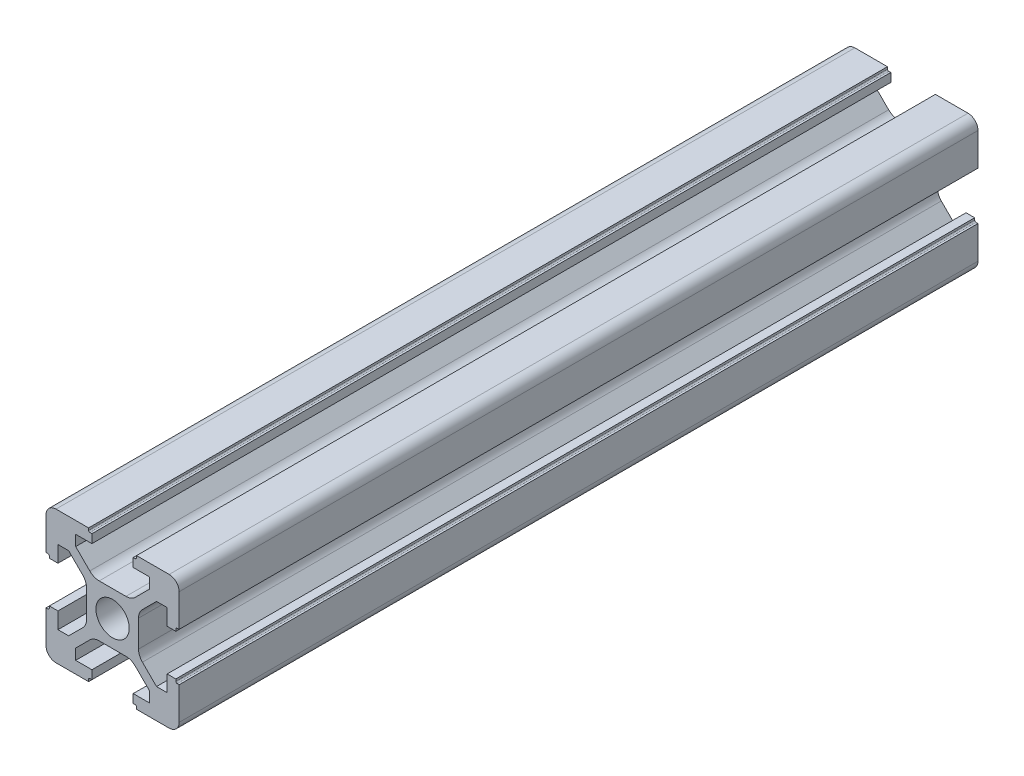
SolidWorks part; units mm, degrees
ref_plane "Спереди" through (0, 0, 0) normal (0, 0, 1) x (1, 0, 0)
ref_plane "Сверху" through (0, 0, 0) normal (0, 1, 0) x (1, 0, 0)
ref_plane "Справа" through (0, 0, 0) normal (1, 0, 0) x (0, 0, -1)
sketch "Sketch1" plane through (0, 0, 0) normal (0, 0, 1) x (1, 0, 0)
  line L0 (0, 10) -> (0, -10) construction
  line L1 (-10, -10) -> (10, -10) construction
  line L2 (-10, -10) -> (-10, 10) construction
  line L3 (-10, 10) -> (10, 10) construction
  line L4 (10, -10) -> (10, 10) construction
  line L5 (-10, -10) -> (10, 10) construction
  line L6 (-10, 10) -> (10, -10) construction
  line L7 (-10, 0) -> (10, 0) construction
  line L8 (0, 3.9) -> (-2.0109, 3.9)
  line L9 (-3.4251, 4.4858) -> (-5.5393, 6.6)
  line L10 (-5.5393, 6.6) -> (-5.5393, 8.2)
  line L11 (-5.5393, 8.2) -> (-3.1, 8.2)
  line L12 (-3.1, 8.2) -> (-3.1, 9.5)
  line L13 (-3.1, 9.5) -> (-3.4, 9.5)
  line L14 (-3.6, 9.7) -> (-3.6, 10)
  line L15 (-3.6, 10) -> (-8.5, 10)
  line L16 (-10, 3.6) -> (-10, 8.5)
  line L17 (-9.7, 3.6) -> (-10, 3.6)
  line L18 (-9.5, 3.1) -> (-9.5, 3.4)
  line L19 (-8.2, 3.1) -> (-9.5, 3.1)
  line L20 (-8.2, 5.5393) -> (-8.2, 3.1)
  line L21 (-6.6, 5.5393) -> (-8.2, 5.5393)
  line L22 (-4.4858, 3.4251) -> (-6.6, 5.5393)
  line L23 (-3.9, 0) -> (-3.9, 2.0109)
  line L24 (3.9, 0) -> (3.9, 2.0109)
  line L25 (4.4858, 3.4251) -> (6.6, 5.5393)
  line L26 (6.6, 5.5393) -> (8.2, 5.5393)
  line L27 (8.2, 5.5393) -> (8.2, 3.1)
  line L28 (8.2, 3.1) -> (9.5, 3.1)
  line L29 (9.5, 3.1) -> (9.5, 3.4)
  line L30 (9.7, 3.6) -> (10, 3.6)
  line L31 (10, 3.6) -> (10, 8.5)
  line L32 (3.6, 10) -> (8.5, 10)
  line L33 (3.6, 9.7) -> (3.6, 10)
  line L34 (3.1, 9.5) -> (3.4, 9.5)
  line L35 (3.1, 8.2) -> (3.1, 9.5)
  line L36 (5.5393, 8.2) -> (3.1, 8.2)
  line L37 (5.5393, 6.6) -> (5.5393, 8.2)
  line L38 (3.4251, 4.4858) -> (5.5393, 6.6)
  line L39 (0, 3.9) -> (2.0109, 3.9)
  line L40 (0, -3.9) -> (2.0109, -3.9)
  line L41 (3.4251, -4.4858) -> (5.5393, -6.6)
  line L42 (5.5393, -6.6) -> (5.5393, -8.2)
  line L43 (5.5393, -8.2) -> (3.1, -8.2)
  line L44 (3.1, -8.2) -> (3.1, -9.5)
  line L45 (3.1, -9.5) -> (3.4, -9.5)
  line L46 (3.6, -9.7) -> (3.6, -10)
  line L47 (3.6, -10) -> (8.5, -10)
  line L48 (10, -3.6) -> (10, -8.5)
  line L49 (9.7, -3.6) -> (10, -3.6)
  line L50 (9.5, -3.1) -> (9.5, -3.4)
  line L51 (8.2, -3.1) -> (9.5, -3.1)
  line L52 (8.2, -5.5393) -> (8.2, -3.1)
  line L53 (6.6, -5.5393) -> (8.2, -5.5393)
  line L54 (4.4858, -3.4251) -> (6.6, -5.5393)
  line L55 (3.9, 0) -> (3.9, -2.0109)
  line L56 (-3.9, 0) -> (-3.9, -2.0109)
  line L57 (-4.4858, -3.4251) -> (-6.6, -5.5393)
  line L58 (-6.6, -5.5393) -> (-8.2, -5.5393)
  line L59 (-8.2, -5.5393) -> (-8.2, -3.1)
  line L60 (-8.2, -3.1) -> (-9.5, -3.1)
  line L61 (-9.5, -3.1) -> (-9.5, -3.4)
  line L62 (-9.7, -3.6) -> (-10, -3.6)
  line L63 (-10, -3.6) -> (-10, -8.5)
  line L64 (-3.6, -10) -> (-8.5, -10)
  line L65 (-3.6, -9.7) -> (-3.6, -10)
  line L66 (-3.1, -9.5) -> (-3.4, -9.5)
  line L67 (-3.1, -8.2) -> (-3.1, -9.5)
  line L68 (-5.5393, -8.2) -> (-3.1, -8.2)
  line L69 (-5.5393, -6.6) -> (-5.5393, -8.2)
  line L70 (-3.4251, -4.4858) -> (-5.5393, -6.6)
  line L71 (0, -3.9) -> (-2.0109, -3.9)
  circle A0 centre (0, 0) radius 2.5
  arc A1 (-8.5, 10) -> (-10, 8.5) centre (-8.5, 8.5) ccw
  arc A2 (-2.0109, 3.9) -> (-3.4251, 4.4858) centre (-2.0109, 5.9) cw
  arc A3 (-3.4, 9.5) -> (-3.6, 9.7) centre (-3.4, 9.7) cw
  arc A4 (-9.5, 3.4) -> (-9.7, 3.6) centre (-9.7, 3.4) ccw
  arc A5 (-3.9, 2.0109) -> (-4.4858, 3.4251) centre (-5.9, 2.0109) ccw
  arc A6 (10, 8.5) -> (8.5, 10) centre (8.5, 8.5) ccw
  arc A7 (3.9, 2.0109) -> (4.4858, 3.4251) centre (5.9, 2.0109) cw
  arc A8 (9.5, 3.4) -> (9.7, 3.6) centre (9.7, 3.4) cw
  arc A9 (3.4, 9.5) -> (3.6, 9.7) centre (3.4, 9.7) ccw
  arc A10 (2.0109, 3.9) -> (3.4251, 4.4858) centre (2.0109, 5.9) ccw
  arc A11 (8.5, -10) -> (10, -8.5) centre (8.5, -8.5) ccw
  arc A12 (2.0109, -3.9) -> (3.4251, -4.4858) centre (2.0109, -5.9) cw
  arc A13 (3.4, -9.5) -> (3.6, -9.7) centre (3.4, -9.7) cw
  arc A14 (9.5, -3.4) -> (9.7, -3.6) centre (9.7, -3.4) ccw
  arc A15 (3.9, -2.0109) -> (4.4858, -3.4251) centre (5.9, -2.0109) ccw
  arc A16 (-10, -8.5) -> (-8.5, -10) centre (-8.5, -8.5) ccw
  arc A17 (-3.9, -2.0109) -> (-4.4858, -3.4251) centre (-5.9, -2.0109) cw
  arc A18 (-9.5, -3.4) -> (-9.7, -3.6) centre (-9.7, -3.4) cw
  arc A19 (-3.4, -9.5) -> (-3.6, -9.7) centre (-3.4, -9.7) ccw
  arc A20 (-2.0109, -3.9) -> (-3.4251, -4.4858) centre (-2.0109, -5.9) ccw
  point P0 (0, 0)
  point P42 (0, 0)
  point P70 (0, 0)
  point P98 (0, 0)
  point P126 (0, 0)
  dimension "D3" = 5
  dimension "D4" = 3
  dimension "D12" = 2
  dimension "D13" = 0.2
  dimension "D1" = 20
  dimension "D2" = 20
  dimension "D5" = 6.2
  dimension "D6" = 7.2
  dimension "D7" = 1.8
  dimension "D8" = 0.5
  dimension "D9" = 3.4
  dimension "D10" = 1.5
  dimension "D11" = 6.1
  dimension "D14" = 4
extrude "Бобышка-Вытянуть1" add sketch "Sketch1" along normal blind 120
